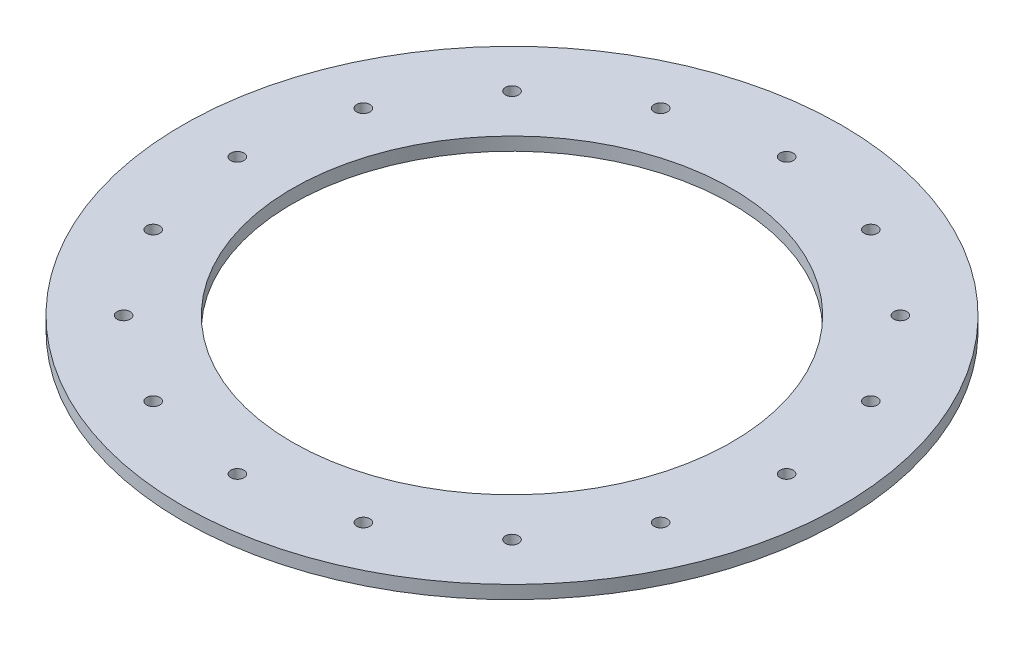
SolidWorks part; units mm, degrees
ref_plane "Front Plane" through (0, 0, 0) normal (0, 0, 1) x (1, 0, 0)
ref_plane "Top Plane" through (0, 0, 0) normal (0, 1, 0) x (1, 0, 0)
ref_plane "Right Plane" through (0, 0, 0) normal (1, 0, 0) x (0, 0, -1)
sketch "Sketch2" plane through (0, 0, 0) normal (0, 1, 0) x (1, 0, 0)
  circle A0 centre (0, 0) radius 25
  circle A1 centre (0, 0) radius 37.5
  circle A2 centre (0, 31.25) radius 0.75
  circle A3 centre (0, 0) radius 31.25 construction
  circle A4 centre (11.9589, 28.8712) radius 0.75
  circle A5 centre (22.0971, 22.0971) radius 0.75
  circle A6 centre (28.8712, 11.9589) radius 0.75
  circle A7 centre (31.25, 0) radius 0.75
  circle A8 centre (28.8712, -11.9589) radius 0.75
  circle A9 centre (22.0971, -22.0971) radius 0.75
  circle A10 centre (11.9589, -28.8712) radius 0.75
  circle A11 centre (0, -31.25) radius 0.75
  circle A12 centre (-11.9589, -28.8712) radius 0.75
  circle A13 centre (-22.0971, -22.0971) radius 0.75
  circle A14 centre (-28.8712, -11.9589) radius 0.75
  circle A15 centre (-31.25, 0) radius 0.75
  circle A16 centre (-28.8712, 11.9589) radius 0.75
  circle A17 centre (-22.0971, 22.0971) radius 0.75
  circle A18 centre (-11.9589, 28.8712) radius 0.75
  point P40 (0, 0)
  dimension "D1" = 50
  dimension "D2" = 75
  dimension "D3" = 62.5
  dimension "D4" = 1.5
  dimension "D5" = 16
extrude "Boss-Extrude2" add sketch "Sketch2" along normal blind 1.5
